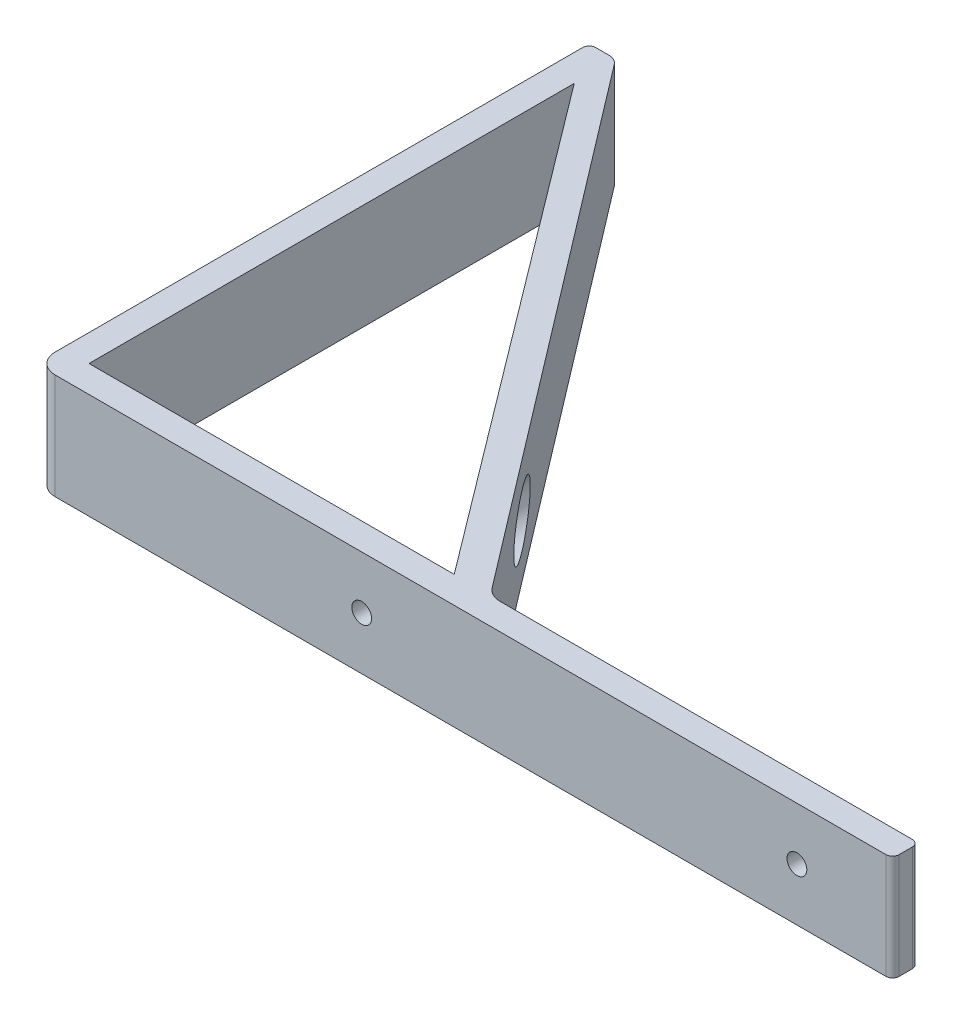
SolidWorks part; units mm, degrees
ref_plane "Front Plane" through (0, 0, 0) normal (0, 0, 1) x (1, 0, 0)
ref_plane "Top Plane" through (0, 0, 0) normal (0, 1, 0) x (1, 0, 0)
ref_plane "Right Plane" through (0, 0, 0) normal (1, 0, 0) x (0, 0, -1)
sketch "Sketch1" plane through (0, 0, 0) normal (0, 1, 0) x (1, 0, 0)
  line L0 (-101.2323, 84.8127) -> (-41.738, 6.7875)
  line L2 (-105.8326, 5.6) -> (-105.8326, 4.6065)
  line L3 (-102.8326, 1.6065) -> (23.1674, 1.6065)
  line L4 (24.1674, 4.6065) -> (24.1674, 2.6065)
  line L6 (-105.8326, 5.6) -> (-105.8326, 84.6)
  line L7 (-104.8326, 85.6) -> (-102.8227, 85.6)
  line L10 (-39.3524, 5.6065) -> (23.1674, 5.6065)
  line L11 (-91.5181, 1.6065) -> (-91.5181, 5.6065)
  line L12 (-101.8326, 33.795) -> (-105.8326, 33.795)
  line L13 (-71.3587, 39.0461) -> (-68.3074, 41.6325)
  line L14 (-101.7424, 5.6445) -> (-45.7708, 5.6445)
  line L15 (-101.7424, 5.6445) -> (-101.7424, 79.0499)
  line L16 (-101.7424, 79.0499) -> (-45.7708, 5.6445)
  arc A0 (-104.8326, 85.6) -> (-105.8326, 84.6) centre (-104.8326, 84.6) ccw
  arc A1 (23.1674, 1.6065) -> (24.1674, 2.6065) centre (23.1674, 2.6065) ccw
  arc A2 (24.1674, 4.6065) -> (23.1674, 5.6065) centre (23.1674, 4.6065) ccw
  arc A3 (-102.8227, 85.6) -> (-101.2323, 84.8127) centre (-102.8227, 83.6) cw
  arc A4 (-41.738, 6.7875) -> (-39.3524, 5.6065) centre (-39.3524, 8.6065) ccw
  arc A5 (-105.8326, 4.6065) -> (-102.8326, 1.6065) centre (-102.8326, 4.6065) ccw
  point P12 (-105.8326, 85.6)
  point P15 (24.1674, 1.6065)
  point P18 (24.1674, 5.6065)
  point P21 (-101.8326, 85.6)
  point P26 (-105.8326, 1.6065)
  dimension "D5" = 1
  dimension "D6" = 2
  dimension "D7" = 3
  dimension "D8" = 3
  dimension "D1" = 4
  dimension "D2" = 130
  dimension "D3" = 80
  dimension "D4" = 4
  dimension "D9" = 4
extrude "Boss-Extrude4" add sketch "Sketch1" along normal blind 16 contours L3 A1 L4 A2 L10 A4 L0 A3 L7 A0 L6 L2 A5
sketch "Sketch2" plane through (0, 16, 0) normal (0, 1, 0) x (1, 0, 0)
  line L0 (-101.7617, 5.6774) -> (-46.3765, 5.6774)
  line L1 (-101.7617, 5.6774) -> (-101.7617, 79.2664)
  line L2 (-101.7617, 79.2664) -> (-46.3765, 5.6774)
  line L3 (-101.7617, 45.1149) -> (-105.8326, 45.1149)
  line L4 (-105.8326, 4.6065) -> (-105.8326, 84.6) construction
  line L5 (-79.5307, 5.6774) -> (-79.5307, 1.6065)
  line L6 (-102.8326, 1.6065) -> (23.1674, 1.6065) construction
  line L7 (-74.2483, 42.71) -> (-71.0111, 45.1784)
  line L8 (-101.2323, 84.8127) -> (-41.738, 6.7875) construction
extrude "Cut-Extrude1" cut sketch "Sketch2" against normal blind 16 contours L2 L0 L1
sketch "Sketch4" plane through (0, 0, -1.6065) normal (0, 0, 1) x (1, 0, 0)
  line L0 (11.1674, 8) -> (23.1674, 8)
  line L3 (23.1674, 16) -> (23.1674, 0) construction
  line L4 (-54.8326, 8) -> (8.1674, 8)
  circle A0 centre (9.6674, 8) radius 1.5
  circle A1 centre (-56.3326, 8) radius 1.5
  dimension "D1" = 12
  dimension "D2" = 63
extrude "Cut-Extrude3" cut sketch "Sketch4" against normal blind 16 contours A1 | A0
sketch "Sketch6" plane through (0, 0, -5.6774) normal (0, 0, -1) x (-1, 0, 0)
  line L0 (57.8326, 8) -> (60.2976, 8) construction
  circle A0 centre (56.2976, 8) radius 4
  circle A2 centre (56.3326, 8) radius 1.5 construction
extrude "Cut-Extrude4" cut sketch "Sketch6" along normal through all contours A0
